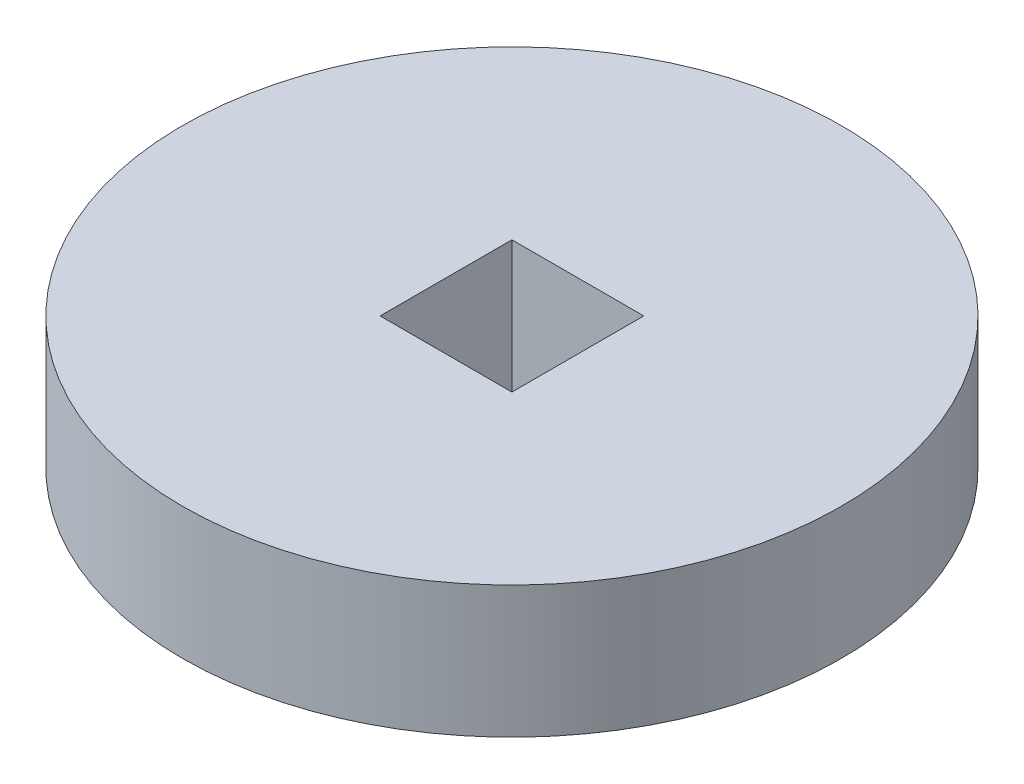
SolidWorks part; units mm, degrees
ref_plane "Front Plane" through (0, 0, 0) normal (0, 0, 1) x (1, 0, 0)
ref_plane "Top Plane" through (0, 0, 0) normal (0, 1, 0) x (1, 0, 0)
ref_plane "Right Plane" through (0, 0, 0) normal (1, 0, 0) x (0, 0, -1)
sketch "Elevator Support Pulleys" plane through (0, 0, 0) normal (0, 1, 0) x (1, 0, 0)
  line L0 (-15.875, 0) -> (15.875, 0) construction
  line L1 (-3.175, 3.175) -> (3.175, 3.175)
  line L2 (-3.175, 3.175) -> (-3.175, -3.175)
  line L3 (-3.175, -3.175) -> (3.175, -3.175)
  line L4 (3.175, 3.175) -> (3.175, -3.175)
  line L5 (-3.175, 3.175) -> (3.175, -3.175) construction
  line L6 (-3.175, -3.175) -> (3.175, 3.175) construction
  circle A0 centre (0, 0) radius 15.875
  dimension "D1" = 31.75
  dimension "D2" = 6.35
extrude "Boss-Extrude1" add sketch "Elevator Support Pulleys" along normal blind 6.35
equation "\"Ball Diameter\"= 1.75in"
equation "\"Sheet Thickness\"= 0.25in"
equation "\"Screw Diameter\"= .17in"
equation "\"Robot Diameter\"= 14in"
equation "\"Castor Screw Diameter\"= 0.22in"
equation "\"Wheel Diameter\" = 4in"
equation "\"Nut Diameter\" = 8.4mm"
equation "\"Nut Height\" = 2.9mm"
equation "\"Screw Height\" = 0.55in"
equation "\"Pulley Diameter\" = 1in"
equation "\"Reactor Height\" = 14in"
equation "\"Elevator Height\" = 11.5in"
equation "\"Elevator Width\" = \"Ball Diameter\" + 0.25in"
equation "\"Elevator Axle Length\" = \"Elevator Width\" + 8*\"Sheet Thickness\""
equation "\"D1@Elevator Support Pulleys\"=\"Elevator Axle Endcap Diameter\""
equation "\"D2@Elevator Support Pulleys\"=\"Sheet Thickness\""
equation "\"D3@Elevator Support Pulleys\"=\"Sheet Thickness\""
equation "\"D1@Boss-Extrude1\"=\"Sheet Thickness\""
equation "\"Elevator Bearing Diameter\" = sqr(2*(\"Sheet Thickness\"^2)) + 0.2in"
equation "\"Elevator Axle Endcap Diameter\" = \"Pulley Diameter\" + 0.25in"
